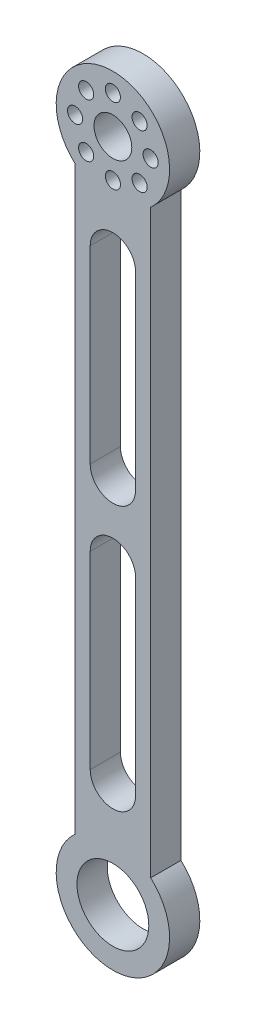
SolidWorks part; units mm, degrees
material "1060 合金"
ref_plane "前视基准面" through (0, 0, 0) normal (0, 0, 1) x (1, 0, 0)
ref_plane "上视基准面" through (0, 0, 0) normal (0, 1, 0) x (1, 0, 0)
ref_plane "右视基准面" through (0, 0, 0) normal (1, 0, 0) x (0, 0, -1)
sketch "草图1" plane through (0, 0, 0) normal (0, 0, 1) x (1, 0, 0)
  line L2 (-10, 76.8197) -> (-10, -76.8197)
  line L4 (10, 76.8197) -> (10, -76.8197)
  line L5 (-10, 88) -> (10, -88) construction
  line L6 (-10, -88) -> (10, 88) construction
  arc A0 (10, 76.8197) -> (-10, 76.8197) centre (0, 88) ccw
  arc A4 (-10, -76.8197) -> (10, -76.8197) centre (0, -88) ccw
  circle A5 centre (0, -88) radius 9.5
  point P0 (0, 0)
  dimension "D3" = 30
  dimension "D4" = 19
  dimension "D5" = 30
  dimension "D1" = 176
  dimension "D2" = 20
extrude "凸台-拉伸1" add sketch "草图1" along normal blind 8
sketch "草图3" plane through (0, 0, 8) normal (0, 0, 1) x (1, 0, 0)
  line L0 (10, 88) -> (0, 88) construction
  line L1 (0, 88) -> (7.0711, 95.0711) construction
  circle A0 centre (0, 88) radius 10 construction
  circle A1 centre (0, 98) radius 2
  circle A2 centre (10, 88) radius 2
  circle A3 centre (0, 78) radius 2
  circle A4 centre (-10, 88) radius 2
  circle A5 centre (7.0711, 95.0711) radius 2
  circle A6 centre (7.0711, 80.9289) radius 2
  circle A7 centre (-7.0711, 80.9289) radius 2
  circle A8 centre (-7.0711, 95.0711) radius 2
  arc A9 (10, 76.8197) -> (-10, 76.8197) centre (0, 88) ccw construction
  point P14 (0, 88)
  point P23 (0, 88)
  dimension "D1" = 20
  dimension "D2" = 4
  dimension "D5" = 4
  dimension "D4" = 45
  dimension "D3" = 4
  dimension "D6" = 4
extrude "切除-拉伸2" cut sketch "草图3" against normal blind 8
sketch "草图4" plane through (0, 0, 8) normal (0, 0, 1) x (1, 0, 0)
  circle A0 centre (0, 88) radius 5
  arc A1 (10, 76.8197) -> (-10, 76.8197) centre (0, 88) ccw construction
  dimension "D1" = 10
extrude "切除-拉伸3" cut sketch "草图4" against normal blind 8
sketch "草图5" plane through (0, 0, 8) normal (0, 0, 1) x (1, 0, 0)
  line L1 (-6, -60) -> (6, -60)
  line L2 (-6, -60) -> (-6, 60)
  line L3 (-6, 60) -> (6, 60)
  line L4 (6, -60) -> (6, 60)
  line L5 (-6, -60) -> (6, 60) construction
  line L6 (-6, 60) -> (6, -60) construction
  arc A1 (-6, 60) -> (6, 60) centre (0, 60) cw
  arc A2 (-6, -60) -> (6, -60) centre (0, -60) ccw
  point P0 (0, 0)
  dimension "D1" = 120
  dimension "D2" = 12
extrude "切除-拉伸4" cut sketch "草图5" against normal blind 10 contours A1 L3 | L1 L4 L3 L2 | L1 A2
sketch "草图6" plane through (0, 0, 8) normal (0, 0, 1) x (1, 0, 0)
  line L0 (-6, 10) -> (-6, -10)
  line L1 (6, 10) -> (6, -10)
  arc A0 (-6, 10) -> (6, 10) centre (0, 10) ccw
  arc A1 (6, -10) -> (-6, -10) centre (0, -10) ccw
  dimension "D1" = 10
  dimension "D2" = 10
extrude "凸台-拉伸2" add sketch "草图6" against normal blind 8
